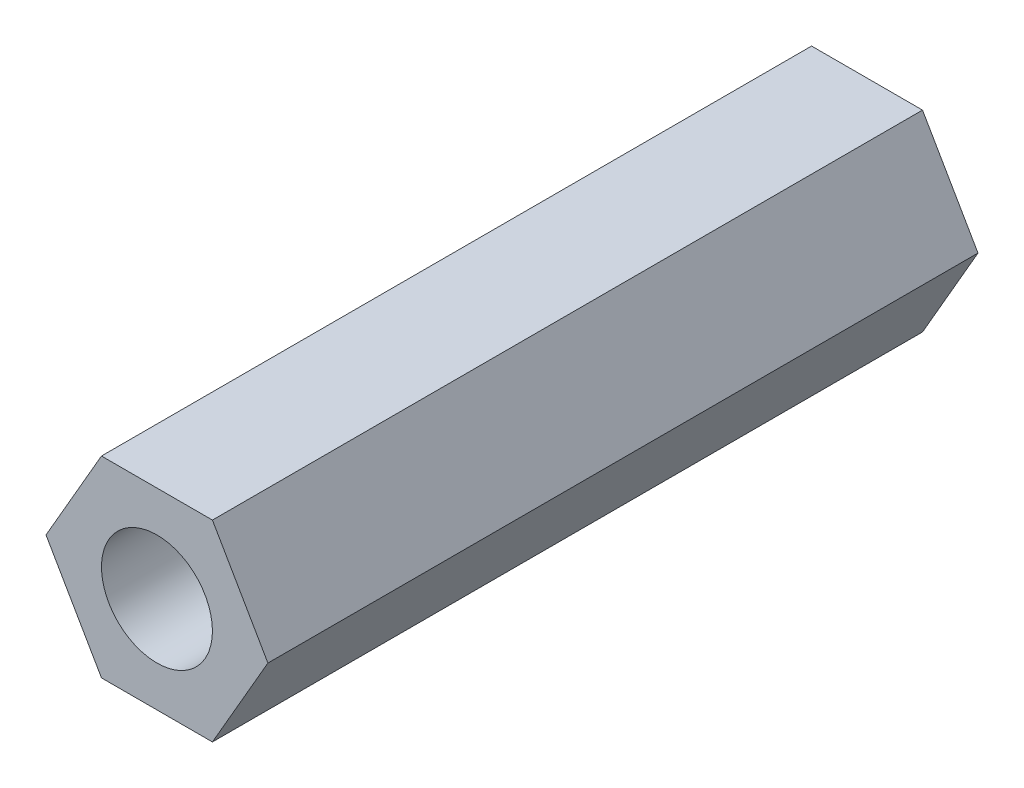
SolidWorks part; units mm, degrees
material "普通碳钢"
ref_plane "前视" through (0, 0, 0) normal (0, 0, 1) x (1, 0, 0)
ref_plane "上视" through (0, 0, 0) normal (0, 1, 0) x (1, 0, 0)
ref_plane "右视" through (0, 0, 0) normal (1, 0, 0) x (0, 0, -1)
sketch "草图1" plane through (0, 0, 0) normal (0, 0, 1) x (1, 0, 0)
  line L0 (0, 0) -> (2.5, 0)
  line L1 (2.5, 0) -> (3.75, -2.1651)
  line L2 (3.75, -2.1651) -> (2.5, -4.3301)
  line L3 (2.5, -4.3301) -> (0, -4.3301)
  line L4 (0, -4.3301) -> (-1.25, -2.1651)
  line L5 (-1.25, -2.1651) -> (0, 0)
  dimension "D1" = 5
  dimension "D2" = 5
extrude "凸台-拉伸1" add sketch "草图1" along normal blind 16
hole_wizard "M3 螺纹孔1" positions "草图3" profile "草图2" tap size "M3" standard "GB" end condition through all
sketch "草图3" plane through (0, 0, 16) normal (0, 0, 1) x (1, 0, 0)
  line L0 (-1.25, -2.1651) -> (3.75, -2.1651) construction
  line L2 (1.25, 0) -> (1.25, -4.3301) construction
  line L3 (2.5, 0) -> (0, 0) construction
  line L4 (0, -4.3301) -> (2.5, -4.3301) construction
  point P0 (1.25, -2.1651)
cosmetic thread "孔螺蚊线1" parameters "D2"=3
sketch "草图2" plane through (1.25, -2.1651, 16) normal (1, 0, 0) x (0, -1, 0)
  line L0 (0, 0) -> (0, 16)
  line L1 (0, 16) -> (1.25, 16)
  line L2 (1.25, 16) -> (1.25, 0)
  line L5 (1.25, 0) -> (0, 0)
  line L11 (0, -6.35) -> (0, 107.95) construction
  dimension "通孔螺纹孔钻头直径" = 2.5
  dimension "通孔螺纹孔钻头深度" = 16
